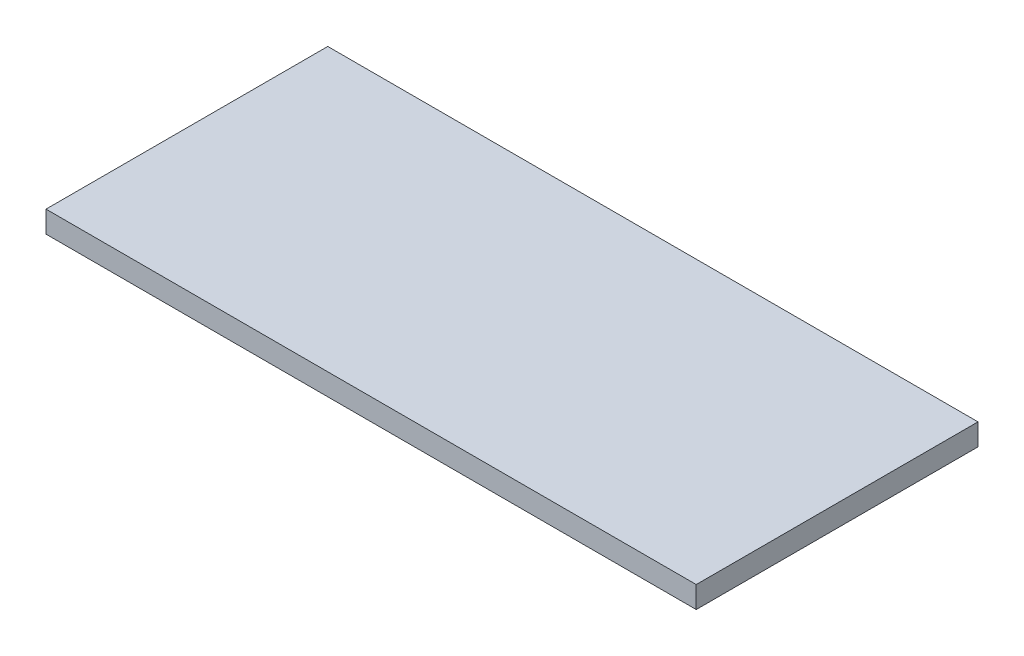
SolidWorks part; units mm, degrees
ref_plane "Front Plane" through (0, 0, 0) normal (0, 0, 1) x (1, 0, 0)
ref_plane "Top Plane" through (0, 0, 0) normal (0, 1, 0) x (1, 0, 0)
ref_plane "Right Plane" through (0, 0, 0) normal (1, 0, 0) x (0, 0, -1)
sketch "Sketch2" plane through (0, 0, 0) normal (0, 1, 0) x (1, 0, 0)
  line L1 (-750, -325) -> (750, -325)
  line L2 (-750, -325) -> (-750, 325)
  line L3 (-750, 325) -> (750, 325)
  line L4 (750, -325) -> (750, 325)
  line L5 (-750, -325) -> (750, 325) construction
  line L6 (-750, 325) -> (750, -325) construction
  point P0 (0, 0)
  dimension "D1" = 1500
  dimension "D2" = 650
extrude "Boss-Extrude2" add sketch "Sketch2" along normal blind 50
